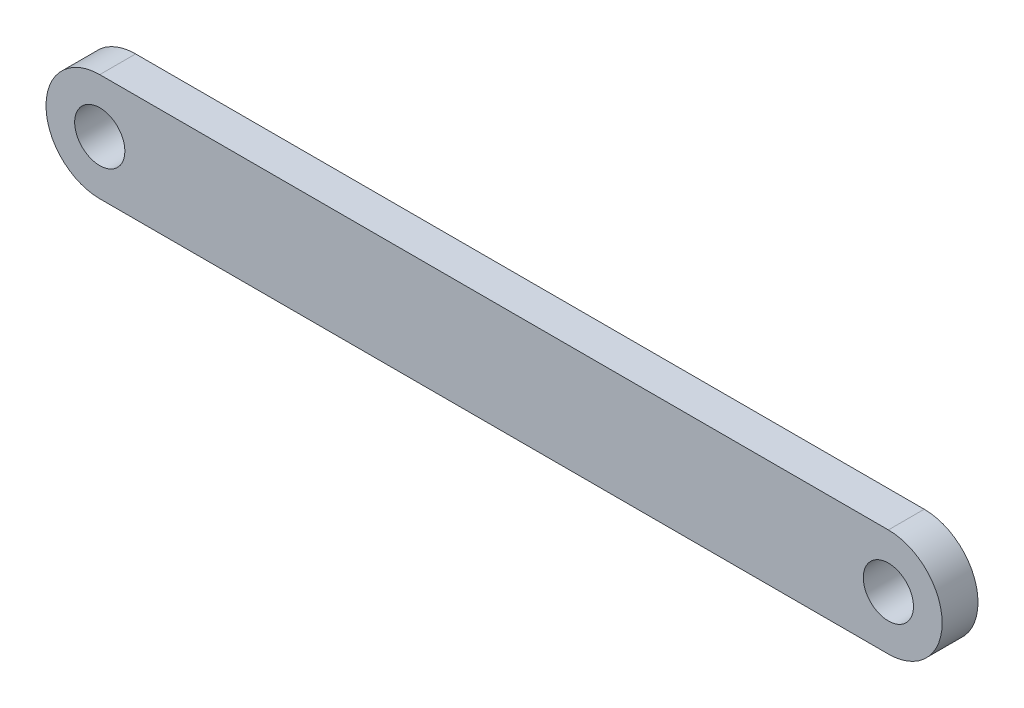
SolidWorks part; units mm, degrees
ref_plane "Front Plane" through (0, 0, 0) normal (0, 0, 1) x (1, 0, 0)
ref_plane "Top Plane" through (0, 0, 0) normal (0, 1, 0) x (1, 0, 0)
ref_plane "Right Plane" through (0, 0, 0) normal (1, 0, 0) x (0, 0, -1)
sketch "Sketch1" plane through (0, 0, 0) normal (0, 0, 1) x (1, 0, 0)
  line L0 (-27.94, 0) -> (27.94, 0)
  line L1 (27.94, -7.62) -> (-27.94, -7.62)
  arc A0 (-27.94, 0) -> (-27.94, -7.62) centre (-27.94, -3.81) ccw
  arc A1 (27.94, -7.62) -> (27.94, 0) centre (27.94, -3.81) ccw
  dimension "D1" = 55.88
  dimension "D2" = 3.81
extrude "Boss-Extrude1" add sketch "Sketch1" along normal blind 2.54
sketch "Sketch2" plane through (0, 0, 2.54) normal (0, 0, 1) x (1, 0, 0)
  circle A0 centre (-27.94, -3.81) radius 1.778
  arc A1 (-27.94, 0) -> (-27.94, -7.62) centre (-27.94, -3.81) ccw construction
  dimension "D1" = 3.556
extrude "Cut-Extrude1" cut sketch "Sketch2" against normal blind 2.54
mirror "Mirror1" about plane through (0, 0, 0) normal (1, 0, 0) of "Cut-Extrude1"
